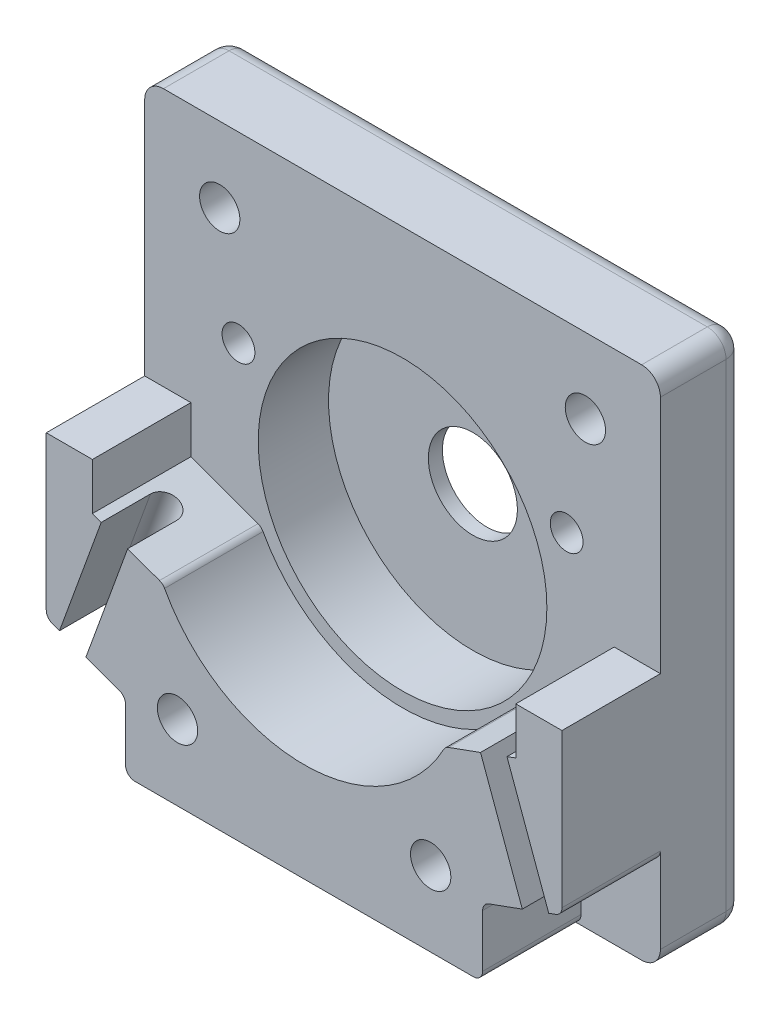
SolidWorks part; units mm, degrees
ref_plane "Front Plane" through (0, 0, 0) normal (0, 0, 1) x (1, 0, 0)
ref_plane "Top Plane" through (0, 0, 0) normal (0, 1, 0) x (1, 0, 0)
ref_plane "Right Plane" through (0, 0, 0) normal (1, 0, 0) x (0, 0, -1)
sketch "Sketch1" plane through (0, 0, 0) normal (0, 0, 1) x (1, 0, 0)
  line L0 (0, 35.5) -> (55, 35.5) construction
  line L1 (0, 0) -> (55, 0)
  line L2 (0, 0) -> (0, 55)
  line L3 (0, 55) -> (55, 55)
  line L4 (55, 0) -> (55, 55)
  line L5 (27.5, 27.5) -> (10, 35.5) construction
  line L6 (27.5, 27.5) -> (45, 35.5) construction
  line L7 (8, 47) -> (47, 47) construction
  line L8 (47, 47) -> (41, 8) construction
  line L9 (41, 8) -> (14, 8) construction
  line L10 (14, 8) -> (8, 47) construction
  circle A0 centre (27.5, 27.5) radius 4.75
  circle A1 centre (8, 47) radius 2.15
  circle A2 centre (47, 47) radius 2.15
  circle A3 centre (41, 8) radius 2.15
  circle A4 centre (14, 8) radius 2.15
  point P5 (0, 27.5)
  point P6 (27.5, 0)
  point P17 (11, 27.5)
  point P18 (27.5, 8)
  point P23 (27.5, 47)
  dimension "D5" = 8
  dimension "D6" = 9.5
  dimension "D7" = 4.3
  dimension "D1" = 55
  dimension "D2" = 55
  dimension "D3" = 8
  dimension "D4" = 35
  dimension "D8" = 8
  dimension "D9" = 14
sketch "Sketch2" plane through (0, 0, 0) normal (0, 1, 0) x (1, 0, 0)
  line L0 (0, 0) -> (0, -1.5) construction
  line L1 (0, -1.5) -> (0, -2) construction
  line L2 (0, -9) -> (0, -19.5) construction
  line L4 (0, -2) -> (0, -9) construction
  dimension "D1" = 1.5
  dimension "D2" = 9
  dimension "D3" = 10.5
  dimension "D4" = 19.5
  dimension "D5" = 7
sketch "Sketch7" plane through (0, 0, 0) normal (0, 0, 1) x (1, 0, 0)
  circle A0 centre (10, 35.5) radius 1.75
  circle A1 centre (45, 35.5) radius 1.75
  dimension "D1" = 3.5
extrude "Boss-Extrude1" add sketch "Sketch1" along normal up to vertex (19.5 mm away) up to point (0, 0, 19.5)
sketch "Sketch3" plane through (0, 0, 0) normal (0, 0, 1) x (1, 0, 0)
  line L0 (36.5, 32.6962) -> (18.5, 32.6962) construction
  line L2 (36.5, 32.6962) -> (27.5, 17.1077) construction
  line L3 (27.5, 17.1077) -> (18.5, 32.6962) construction
  line L4 (18.5, 32.6962) -> (27.5, 27.5) construction
  line L5 (42.1292, 35.9462) -> (43.5148, 36.7462) construction
  line L6 (36.5, 32.6962) -> (27.5, 27.5) construction
  line L8 (27.5, 27.5) -> (27.5, 17.1077) construction
  line L9 (40.8301, 35.1962) -> (42.1292, 35.9462) construction
  circle A0 centre (27.5, 27.5) radius 4.25 construction
  circle A2 centre (36.5, 32.6962) radius 6.5 construction
  circle A3 centre (27.5, 17.1077) radius 6.5 construction
  circle A4 centre (18.5, 32.6962) radius 6.5 construction
  circle A6 centre (36.5, 32.6962) radius 2 construction
  circle A7 centre (27.5, 17.1077) radius 2 construction
  circle A8 centre (18.5, 32.6962) radius 2 construction
  circle A9 centre (27.5, 27.5) radius 18.4923 construction
  circle A10 centre (27.5, 27.5) radius 15.3923 construction
  circle A11 centre (18.5, 32.6962) radius 4.25 construction
  circle A13 centre (36.5, 32.6962) radius 4.25 construction
  circle A14 centre (27.5, 17.1077) radius 4.25 construction
  dimension "D1" = 13
  dimension "D2" = 8.5
  dimension "D3" = 4
  dimension "D6" = 8.5
  dimension "D4" = 1.6
  dimension "D5" = 1.5
  dimension "D7" = 18
sketch "Sketch11" plane through (0, 0, 0) normal (0, 0, 1) x (1, 0, 0)
  line L0 (10.0496, 50.55) -> (5.9504, 50.55)
  line L1 (5.9504, 50.55) -> (3.9008, 47)
  line L2 (3.9008, 47) -> (5.9504, 43.45)
  line L3 (5.9504, 43.45) -> (10.0496, 43.45)
  line L4 (10.0496, 43.45) -> (12.0992, 47)
  line L5 (12.0992, 47) -> (10.0496, 50.55)
  line L6 (42.9008, 47) -> (44.9504, 50.55)
  line L7 (44.9504, 50.55) -> (49.0496, 50.55)
  line L8 (49.0496, 50.55) -> (51.0992, 47)
  line L9 (51.0992, 47) -> (49.0496, 43.45)
  line L10 (49.0496, 43.45) -> (44.9504, 43.45)
  line L11 (44.9504, 43.45) -> (42.9008, 47)
  line L12 (38.9504, 11.55) -> (43.0496, 11.55)
  line L13 (43.0496, 11.55) -> (45.0992, 8)
  line L14 (45.0992, 8) -> (43.0496, 4.45)
  line L15 (43.0496, 4.45) -> (38.9504, 4.45)
  line L16 (38.9504, 4.45) -> (36.9008, 8)
  line L17 (36.9008, 8) -> (38.9504, 11.55)
  line L18 (11.9504, 11.55) -> (16.0496, 11.55)
  line L19 (16.0496, 11.55) -> (18.0992, 8)
  line L20 (18.0992, 8) -> (16.0496, 4.45)
  line L21 (16.0496, 4.45) -> (11.9504, 4.45)
  line L22 (11.9504, 4.45) -> (9.9008, 8)
  line L23 (9.9008, 8) -> (11.9504, 11.55)
  circle A0 centre (8, 47) radius 4.0992 construction
  circle A1 centre (47, 47) radius 4.0992 construction
  circle A2 centre (41, 8) radius 4.0992 construction
  circle A3 centre (14, 8) radius 4.0992 construction
  dimension "D1" = 7.1
extrude "Cut-Extrude10" cut sketch "Sketch11" along normal blind 3.5
ref_plane "Plane1" through (0, 0, 19.5) normal (0, 0, 1) x (1, 0, 0)
sketch "Sketch5" plane through (0, 0, 19.5) normal (0, 0, 1) x (1, 0, 0)
  circle A0 centre (27.5, 27.5) radius 15.3923
  circle A3 centre (27.5, 27.5) radius 15.3923 construction
extrude "Cut-Extrude2" cut sketch "Sketch5" against normal up to vertex (18 mm away) up to point (0, 0, 1.5)
sketch "Sketch6" plane through (0, 0, 19.5) normal (0, 0, 1) x (1, 0, 0)
  line L0 (12.4431, 19.7327) -> (4.9255, 22.4689)
  line L1 (13.7312, 26.1957) -> (1.249, -8.0991) construction
  line L2 (0, 0) -> (55, 0) construction
  line L3 (8.4572, 0) -> (46.5428, 0)
  line L4 (0, 0) -> (0, 55) construction
  line L5 (1.4095, 9.8849) -> (7.0477, 7.8328) construction
  line L6 (0, 10.398) -> (0, 27.4689)
  line L7 (42.5569, 19.7327) -> (50.0745, 22.4689)
  line L8 (0, 0) -> (55, 0) construction
  line L9 (5.8652, 22.1268) -> (11.5034, 20.0747) construction
  line L10 (42.1292, 35.9462) -> (42.1725, 35.9712) construction
  line L11 (36.5, 32.6962) -> (27.5, 27.5) construction
  line L13 (0, 27.4689) -> (4.9255, 27.4689)
  line L14 (55, 0) -> (55, 55) construction
  line L15 (55, 27.4689) -> (55, 10.398)
  line L16 (55, 0) -> (55, 55) construction
  line L17 (4.9255, 27.4689) -> (4.9255, 22.4689)
  line L18 (10.1229, 33.8247) -> (-2.3593, -0.47) construction
  line L19 (0, 10.398) -> (8.4572, 7.3198)
  line L20 (8.4572, 7.3198) -> (8.4572, 0)
  line L21 (0, 53) -> (0, 27.9689) construction
  line L22 (55, 55) -> (0, 55) construction
  line L23 (55, 10.398) -> (46.5428, 7.3198)
  line L24 (46.5428, 7.3198) -> (46.5428, 0)
  line L25 (0, 55) -> (0, 0) construction
  line L26 (50.0745, 22.4689) -> (50.0745, 27.4689)
  line L27 (50.0745, 27.4689) -> (55, 27.4689)
  arc A0 (12.4431, 19.7327) -> (42.5569, 19.7327) centre (27.5, 27.5) ccw
  circle A1 centre (27.5, 27.5) radius 18.4923 construction
  circle A3 centre (36.5, 32.6962) radius 6.5 construction
  point P36 (4.2286, 8.8589)
  point P39 (4.2286, 8.8589)
  point P40 (8.6843, 21.1008)
  point P43 (8.6843, 21.1008)
  dimension "D1" = 8
  dimension "D2" = 6
  dimension "D3" = 0.05
  dimension "D4" = 13.9808
  dimension "D5" = 70
  dimension "D6" = 9
  dimension "D7" = 5
extrude "Cut-Extrude3" cut sketch "Sketch6" against normal up to vertex (10.5 mm away) flip side to cut up to point (0, 0, 9)
extrude "Cut-Extrude4" cut sketch "Sketch7" along normal up to vertex (9 mm away) up to point (0, 0, 9)
ref_plane "Plane3" through (3.3418, 9.1816, 0) normal (-0.342, -0.9397, 0) x (0, 0, 1)
sketch "Sketch9" plane through (3.3418, 9.1816, 0) normal (-0.342, -0.9397, 0) x (0, 0, 1)
  line L0 (9, 3.5563) -> (9, -5.4437) construction
  line L1 (9, 3.5563) -> (9, 0) construction
  line L2 (14.25, 2.0563) -> (19.5, 2.0563)
  line L3 (19.5, -4.9437) -> (19.5, 3.0563) construction
  line L4 (19.5, 2.0563) -> (19.5, -0.9437)
  line L5 (19.5, -0.9437) -> (14.25, -0.9437)
  line L7 (19.5, 3.5563) -> (19.5, -5.4437) construction
  arc A0 (14.25, 2.0563) -> (14.25, -0.9437) centre (14.25, 0.5563) ccw
  point P0 (9, -0.9437)
  dimension "D2" = 3
  dimension "D1" = 5.25
extrude "Cut-Extrude6" cut sketch "Sketch9" against normal up to next contours A0
ref_plane "Plane4" through (3.0919, -8.495, 0) normal (0.342, -0.9397, 0) x (0, 0, -1)
sketch "Sketch10" plane through (3.0919, -8.495, 0) normal (0.342, -0.9397, 0) x (0, 0, -1)
  line L0 (-9, 46.2394) -> (-9, 55.2394) construction
  line L1 (-9, 51.6831) -> (-9, 55.2394) construction
  line L2 (-14.25, 53.7394) -> (-19.5, 53.7394)
  line L3 (-19.5, 46.7394) -> (-19.5, 54.7394) construction
  line L4 (-19.5, 53.7394) -> (-19.5, 50.7394)
  line L5 (-19.5, 50.7394) -> (-14.25, 50.7394)
  arc A0 (-14.25, 50.7394) -> (-14.25, 53.7394) centre (-14.25, 52.2394) ccw
  point P0 (-9, 50.7394)
  dimension "D2" = 3
  dimension "D1" = 5.25
extrude "Cut-Extrude11" cut sketch "Sketch10" against normal up to next
fillet "Fillet2" radius 2 8 edges at (0, 0, 4.5) (27.5, 0, 0) (55, 0, 4.5) (55, 27.5, 0) (27.5, 55, 0) (0, 55, 4.5) (0, 27.5, 0) (55, 55, 4.5)
fillet "Fillet3" radius 1 8 edges at (55, 10.398, 14.25) (0, 10.398, 14.25) (46.5428, 0, 14.25) (8.4572, 0, 14.25) (46.5428, 7.3198, 14.25) (8.4572, 7.3198, 14.25) (42.5569, 19.7327, 14.25) (12.4431, 19.7327, 14.25)
